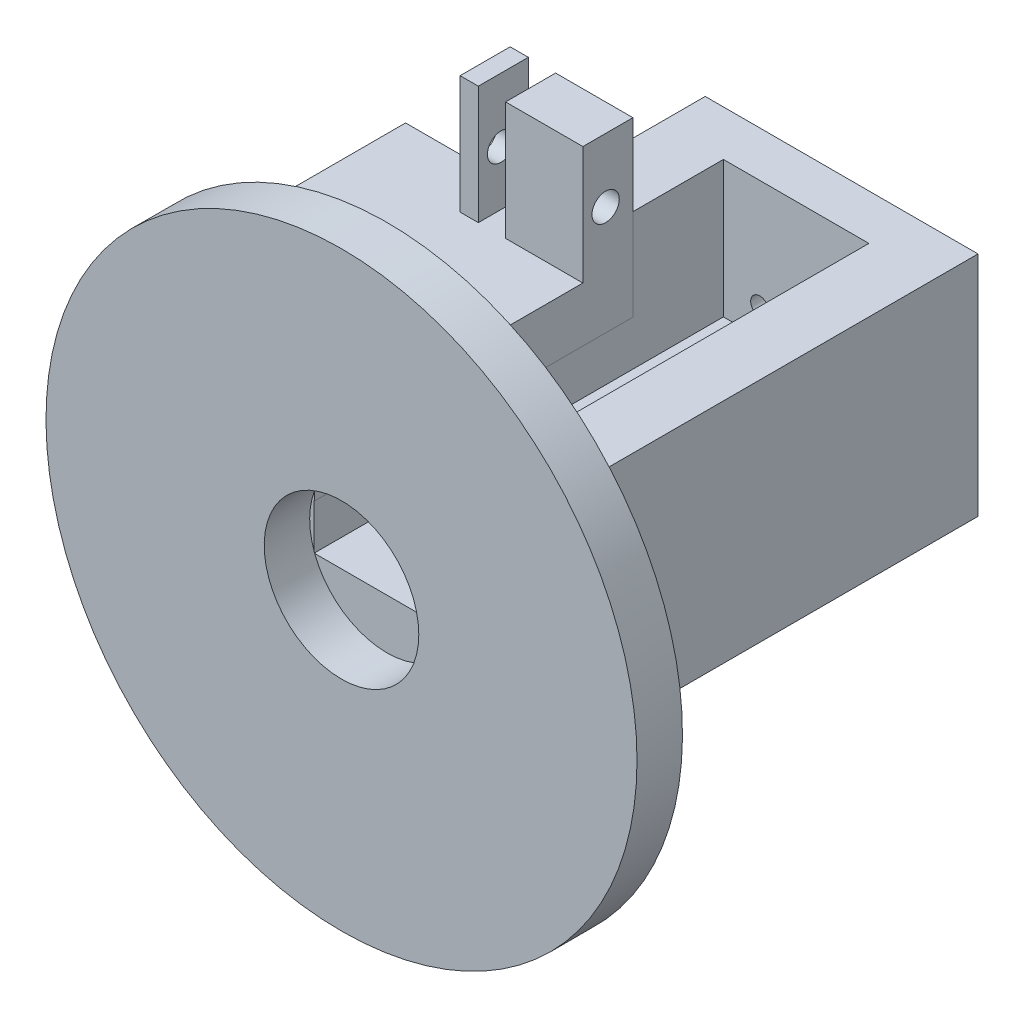
SolidWorks part; units mm, degrees
ref_plane "Alzado" through (0, 0, 0) normal (0, 0, 1) x (1, 0, 0)
ref_plane "Planta" through (0, 0, 0) normal (0, 1, 0) x (1, 0, 0)
ref_plane "Vista lateral" through (0, 0, 0) normal (1, 0, 0) x (0, 0, -1)
sketch "Croquis1" plane through (0, 0, 0) normal (0, 0, 1) x (1, 0, 0)
  circle A0 centre (0, 0) radius 8.5
  circle A1 centre (0, 0) radius 32.5
  dimension "D1" = 65
  dimension "D2" = 17
extrude "Saliente-Extruir1" add sketch "Croquis1" along normal blind 5
sketch "Croquis3" plane through (0, 0, 0) normal (0, 0, -1) x (-1, 0, 0)
  line L1 (-15, -3) -> (15, -3)
  line L2 (-15, -3) -> (-15, -13)
  line L3 (-15, -13) -> (15, -13)
  line L4 (15, -3) -> (15, -13)
  dimension "D1" = 30
  dimension "D2" = 15
  dimension "D3" = 10
  dimension "2" = 3
extrude "Saliente-Extruir5" add sketch "Croquis3" along normal blind 50
sketch "Croquis4" plane through (0, -3, 0) normal (0, 1, 0) x (1, 0, 0)
  line L0 (32.5, 0) -> (-32.5, 0) construction
  line L1 (-15, 50) -> (-8, 50)
  line L2 (-15, 50) -> (-15, 0)
  line L3 (-15, 0) -> (-8, 0)
  line L4 (-8, 50) -> (-8, 0)
  line L5 (-7.953, 0) -> (7.953, 0) construction
  line L6 (15, 50) -> (8, 50)
  line L7 (15, 50) -> (15, 0)
  line L8 (15, 0) -> (8, 0)
  line L9 (8, 50) -> (8, 0)
  dimension "D1" = 16
  dimension "D2" = 8
extrude "Saliente-Extruir6" add sketch "Croquis4" along normal blind 5
sketch "Croquis5" plane through (0, 2, 0) normal (0, 1, 0) x (1, 0, 0)
  line L1 (-7.953, 0) -> (-32.953, 0)
  line L2 (-7.953, 0) -> (-7.953, 35)
  line L3 (-7.953, 35) -> (-32.953, 35)
  line L4 (-32.953, 0) -> (-32.953, 35)
  dimension "D1" = 35
  dimension "D2" = 25
extrude "Saliente-Extruir7" add sketch "Croquis5" along normal blind 6
sketch "Croquis6" plane through (0, 8, 0) normal (0, 1, 0) x (1, 0, 0)
  line L0 (-7.953, 35) -> (-32.953, 35) construction
  line L1 (-7.953, 35) -> (-16.453, 35)
  line L2 (-7.953, 35) -> (-7.953, 29.5)
  line L3 (-7.953, 29.5) -> (-16.453, 29.5)
  line L4 (-16.453, 35) -> (-16.453, 29.5)
  line L5 (-19.453, 35) -> (-21.453, 35)
  line L6 (-19.453, 35) -> (-19.453, 29.5)
  line L7 (-19.453, 29.5) -> (-21.453, 29.5)
  line L8 (-21.453, 35) -> (-21.453, 29.5)
  line L9 (-31.5, 0) -> (-7.953, 0) construction
  line L10 (-7.953, 0) -> (-16.453, 0)
  line L11 (-7.953, 0) -> (-7.953, 7)
  line L12 (-7.953, 7) -> (-16.453, 7)
  line L13 (-16.453, 0) -> (-16.453, 7)
  line L14 (-19.453, 7) -> (-21.453, 7)
  line L15 (-19.453, 7) -> (-19.453, 0)
  line L16 (-19.453, 0) -> (-21.453, 0)
  line L17 (-21.453, 7) -> (-21.453, 0)
  dimension "D1" = 5.5
  dimension "D2" = 8.5
  dimension "D3" = 2
  dimension "D4" = 3
  dimension "D5" = 7
  dimension "D6" = 7
  dimension "D7" = 8.5
extrude "Saliente-Extruir8" add sketch "Croquis6" along normal blind 13
sketch "Croquis7" plane through (-7.953, 0, 0) normal (1, 0, 0) x (0, 0, -1)
  line L0 (7, 8) -> (29.5, 8) construction
  line L1 (7, 21) -> (7, 8) construction
  line L2 (29.5, 21) -> (29.5, 8) construction
  circle A0 centre (32, 14) radius 1.5
  circle A1 centre (4, 14) radius 1.5
  dimension "D3" = 3
  dimension "D4" = 3
  dimension "D1" = 6
  dimension "D2" = 6
  dimension "D5" = 3
  dimension "D6" = 2.5
extrude "Cortar-Extruir1" cut sketch "Croquis7" against normal blind 20
sketch "Croquis8" plane through (0, -3, 0) normal (0, 1, 0) x (1, 0, 0)
  line L0 (-8, 35) -> (-8, 50) construction
  line L1 (8, 50) -> (-8, 50)
  line L2 (8, 50) -> (8, 45)
  line L3 (8, 45) -> (-8, 45)
  line L4 (-8, 50) -> (-8, 45)
  dimension "D1" = 5
extrude "Saliente-Extruir9" add sketch "Croquis8" along normal blind 5
sketch "Croquis10" plane through (0, 2, 0) normal (0, 1, 0) x (1, 0, 0)
  line L0 (8, 0) -> (15, 0)
  line L1 (15, 0) -> (15, 50)
  line L2 (15, 50) -> (-15, 50)
  line L3 (-15, 50) -> (-15, 35)
  line L4 (-7.953, 35) -> (-16.453, 35) construction
  line L5 (-15, 35) -> (-8, 35) construction
  line L6 (-15, 35) -> (-8, 35)
  line L7 (-8, 0) -> (-8, 45) construction
  line L8 (-8, 35) -> (-8, 45)
  line L9 (-8, 45) -> (8, 45)
  line L10 (8, 45) -> (8, 0)
extrude "Saliente-Extruir10" add sketch "Croquis10" along normal blind 10
sketch "Croquis11" plane through (0, 0, -50) normal (0, 0, -1) x (-1, 0, 0)
  line L0 (-18.6088, 0) -> (27.7371, 0) construction
  circle A0 centre (-4, 0) radius 1
  circle A1 centre (-12, 0) radius 1
  circle A2 centre (4, 0) radius 1
  circle A3 centre (12, 0) radius 1
  dimension "D1" = 2
  dimension "D2" = 2
  dimension "D3" = 2
  dimension "D4" = 2
  dimension "D5" = 8
  dimension "D6" = 8
  dimension "D7" = 4
  dimension "D8" = 4
extrude "Cortar-Extruir2" cut sketch "Croquis11" against normal blind 5
sketch "Croquis12" plane through (0, 0, -50) normal (0, 0, -1) x (-1, 0, 0)
  point P0 (0, 0)
sketch "Croquis13" plane through (0, 0, -50) normal (0, 0, -1) x (-1, 0, 0)
  circle A0 centre (0, 0) radius 1.5
  dimension "D1" = 3
extrude "Cortar-Extruir3" cut sketch "Croquis13" against normal blind 10
